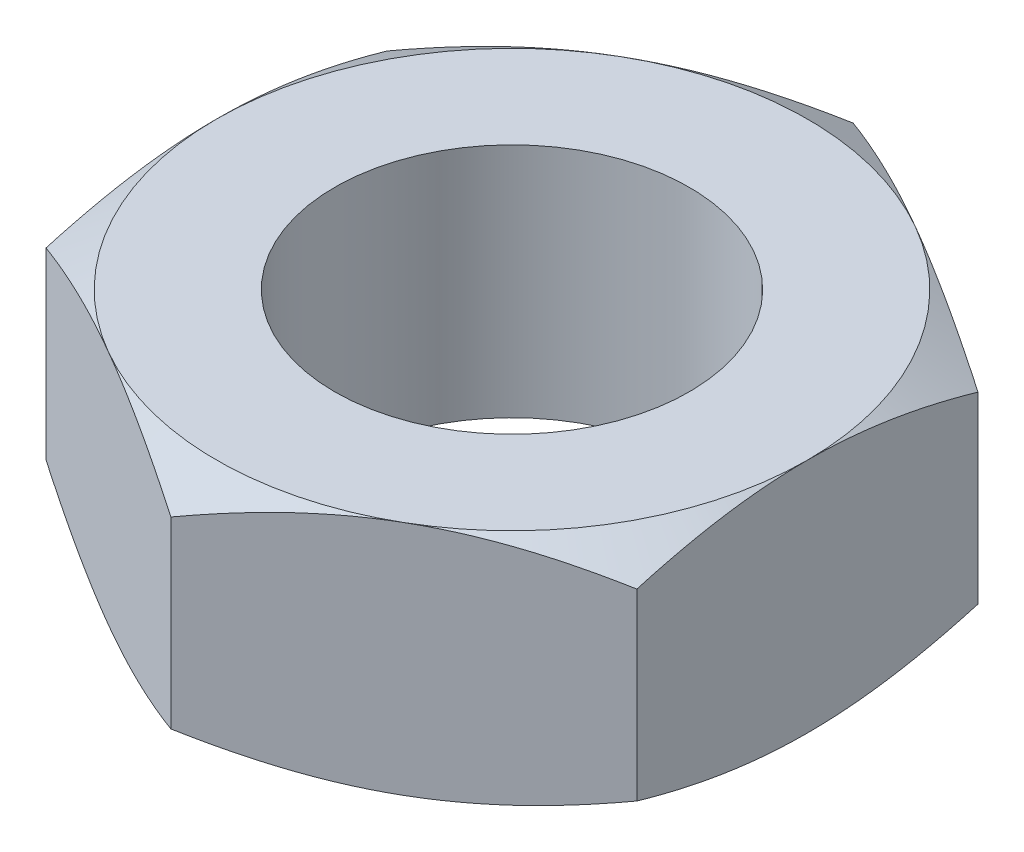
SolidWorks part; units mm, degrees
ref_plane "Front Plane" through (0, 0, 0) normal (0, 0, 1) x (1, 0, 0)
ref_plane "Top Plane" through (0, 0, 0) normal (0, 1, 0) x (1, 0, 0)
ref_plane "Right Plane" through (0, 0, 0) normal (1, 0, 0) x (0, 0, -1)
sketch "Sketch1" plane through (0, 0, 0) normal (0, 1, 0) x (1, 0, 0)
  line L1 (0, 2.8868) -> (-2.5, 1.4434)
  line L2 (-2.5, 1.4434) -> (-2.5, -1.4434)
  line L3 (-2.5, -1.4434) -> (0, -2.8868)
  line L4 (0, -2.8868) -> (2.5, -1.4434)
  line L5 (2.5, -1.4434) -> (2.5, 1.4434)
  line L6 (2.5, 1.4434) -> (0, 2.8868)
  circle A0 centre (0, 0) radius 1.5
  circle A1 centre (0, 0) radius 2.5 construction
  dimension "D1" = 3
  dimension "D2" = 5
extrude "Boss-Extrude1" add sketch "Sketch1" along normal blind 2
sketch "Sketch2" plane through (0, 2, 0) normal (0, 1, 0) x (1, 0, 0)
  circle A0 centre (0, 0) radius 2.5 construction
  circle A1 centre (0, 0) radius 2.5
extrude "Cut-Extrude1" cut sketch "Sketch2" against normal blind 2 draft 60 flip side to cut
sketch "Sketch3" plane through (0, 0, 0) normal (0, -1, 0) x (1, 0, 0)
  circle A0 centre (0, 0) radius 2.5 construction
  circle A1 centre (0, 0) radius 2.5
extrude "Cut-Extrude2" cut sketch "Sketch3" against normal blind 2 draft 60 flip side to cut
